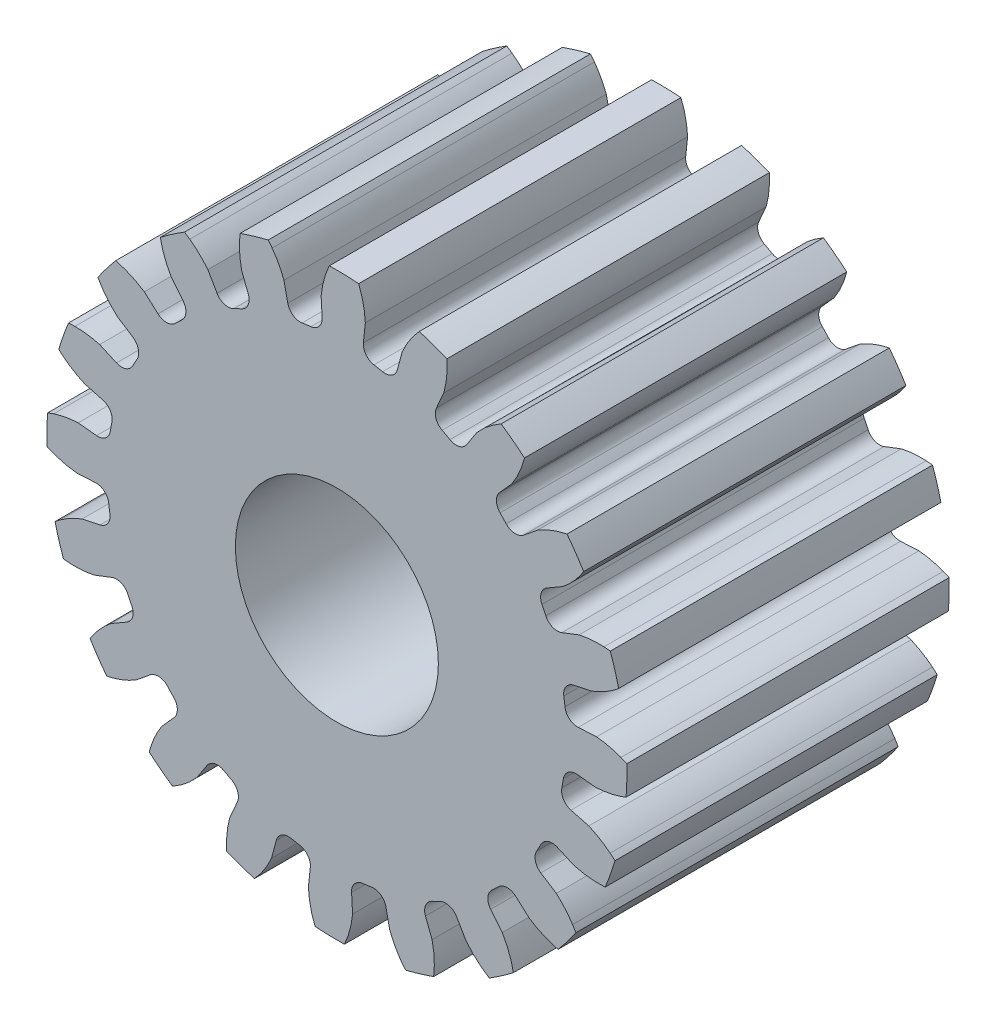
SolidWorks part; units mm, degrees
ref_plane "Front Plane" through (0, 0, 0) normal (0, 0, 1) x (1, 0, 0)
ref_plane "Top Plane" through (0, 0, 0) normal (0, 1, 0) x (1, 0, 0)
ref_plane "Right Plane" through (0, 0, 0) normal (1, 0, 0) x (0, 0, -1)
sketch "Sketch1" plane through (0, 0, 0) normal (0, 0, 1) x (1, 0, 0)
  line L0 (541.9192, -238.0328) -> (542.2005, -237.8042) construction
  line L1 (542.6706, -238.2979) -> (542.4285, -238.5677) construction
  line L2 (543.12, -239.0965) -> (543.3169, -238.7922) construction
  line L3 (543.9165, -239.1165) -> (543.7696, -239.4479) construction
  line L4 (544.5907, -239.7371) -> (544.6839, -239.3868) construction
  line L5 (545.3543, -239.5099) -> (545.317, -239.8705) construction
  line L6 (546.1873, -239.8919) -> (546.1678, -239.5299) construction
  line L7 (546.8434, -239.4398) -> (546.9194, -239.7943) construction
  line L8 (547.7537, -239.5456) -> (547.6232, -239.2074) construction
  line L9 (548.238, -238.913) -> (548.4197, -239.2266) construction
  line L10 (549.1364, -238.7323) -> (548.9078, -238.451) construction
  line L11 (549.4014, -237.981) -> (549.6712, -238.2231) construction
  line L12 (550.2001, -237.5316) -> (549.8957, -237.3346) construction
  line L13 (550.22, -236.7351) -> (550.5514, -236.882) construction
  line L14 (550.8406, -236.0609) -> (550.4903, -235.9676) construction
  line L15 (550.6134, -235.2972) -> (550.974, -235.3345) construction
  line L16 (550.9954, -234.4642) -> (550.6334, -234.4838) construction
  line L17 (550.5433, -233.8081) -> (550.8978, -233.7322) construction
  line L18 (550.6492, -232.8979) -> (550.311, -233.0283) construction
  line L19 (550.0165, -232.4136) -> (550.3301, -232.2318) construction
  line L20 (549.8359, -231.5152) -> (549.5545, -231.7438) construction
  line L21 (549.0845, -231.2501) -> (549.3266, -230.9803) construction
  line L22 (548.6351, -230.4515) -> (548.4382, -230.7558) construction
  line L23 (547.8386, -230.4316) -> (547.9855, -230.1002) construction
  line L24 (547.1644, -229.8109) -> (547.0712, -230.1612) construction
  line L25 (546.4007, -230.0381) -> (546.438, -229.6775) construction
  line L26 (545.5677, -229.6562) -> (545.5873, -230.0181) construction
  line L27 (544.9116, -230.1082) -> (544.8357, -229.7538) construction
  line L28 (544.0014, -230.0024) -> (544.1319, -230.3406) construction
  line L29 (543.5171, -230.6351) -> (543.3353, -230.3214) construction
  line L30 (542.6187, -230.8157) -> (542.8473, -231.097) construction
  line L31 (542.3536, -231.567) -> (542.0838, -231.3249) construction
  line L32 (541.555, -232.0164) -> (541.8594, -232.2134) construction
  line L33 (541.5351, -232.813) -> (541.2037, -232.6661) construction
  line L34 (540.9144, -233.4871) -> (541.2647, -233.5804) construction
  line L35 (541.1416, -234.2508) -> (540.7811, -234.2135) construction
  line L36 (540.7597, -235.0838) -> (541.1217, -235.0642) construction
  line L37 (541.2117, -235.7399) -> (540.8573, -235.8159) construction
  line L38 (541.1059, -236.6501) -> (541.4441, -236.5197) construction
  line L39 (541.7386, -237.1344) -> (541.4249, -237.3162) construction
  line L40 (541.9192, -238.0328) -> (542.2005, -237.8042)
  line L41 (542.6706, -238.2979) -> (542.4285, -238.5677)
  line L42 (543.12, -239.0965) -> (543.3169, -238.7922)
  line L43 (543.9165, -239.1165) -> (543.7696, -239.4479)
  line L44 (544.5907, -239.7371) -> (544.6839, -239.3868)
  line L45 (545.3543, -239.5099) -> (545.317, -239.8705)
  line L46 (546.1873, -239.8919) -> (546.1678, -239.5299)
  line L47 (546.8434, -239.4398) -> (546.9194, -239.7943)
  line L48 (547.7537, -239.5456) -> (547.6232, -239.2074)
  line L49 (548.238, -238.913) -> (548.4197, -239.2266)
  line L50 (549.1364, -238.7323) -> (548.9078, -238.451)
  line L51 (549.4014, -237.981) -> (549.6712, -238.2231)
  line L52 (550.2001, -237.5316) -> (549.8957, -237.3346)
  line L53 (550.22, -236.7351) -> (550.5514, -236.882)
  line L54 (550.8406, -236.0609) -> (550.4903, -235.9676)
  line L55 (550.6134, -235.2972) -> (550.974, -235.3345)
  line L56 (550.9954, -234.4642) -> (550.6334, -234.4838)
  line L57 (550.5433, -233.8081) -> (550.8978, -233.7322)
  line L58 (550.6492, -232.8979) -> (550.311, -233.0283)
  line L59 (550.0165, -232.4136) -> (550.3301, -232.2318)
  line L60 (549.8359, -231.5152) -> (549.5545, -231.7438)
  line L61 (549.0845, -231.2501) -> (549.3266, -230.9803)
  line L62 (548.6351, -230.4515) -> (548.4382, -230.7558)
  line L63 (547.8386, -230.4316) -> (547.9855, -230.1002)
  line L64 (547.1644, -229.8109) -> (547.0712, -230.1612)
  line L65 (546.4007, -230.0381) -> (546.438, -229.6775)
  line L66 (545.5677, -229.6562) -> (545.5873, -230.0181)
  line L67 (544.9116, -230.1082) -> (544.8357, -229.7538)
  line L68 (544.0014, -230.0024) -> (544.1319, -230.3406)
  line L69 (543.5171, -230.6351) -> (543.3353, -230.3214)
  line L70 (542.6187, -230.8157) -> (542.8473, -231.097)
  line L71 (542.3536, -231.567) -> (542.0838, -231.3249)
  line L72 (541.555, -232.0164) -> (541.8594, -232.2134)
  line L73 (541.5351, -232.813) -> (541.2037, -232.6661)
  line L74 (540.9144, -233.4871) -> (541.2647, -233.5804)
  line L75 (541.1416, -234.2508) -> (540.7811, -234.2135)
  line L76 (540.7597, -235.0838) -> (541.1217, -235.0642)
  line L77 (541.2117, -235.7399) -> (540.8573, -235.8159)
  line L78 (541.1059, -236.6501) -> (541.4441, -236.5197)
  line L79 (541.7386, -237.1344) -> (541.4249, -237.3162)
  arc A0 (545.4481, -240.4729) -> (546.0269, -240.4871) centre (545.8775, -234.774) ccw construction
  arc A1 (547.2301, -240.3266) -> (547.785, -240.1613) centre (545.8775, -234.774) ccw construction
  arc A2 (548.8798, -239.6369) -> (549.3564, -239.3082) centre (545.8775, -234.774) ccw construction
  arc A3 (550.2356, -238.4712) -> (550.5873, -238.0112) centre (545.8775, -234.774) ccw construction
  arc A4 (551.1647, -236.9435) -> (551.3571, -236.3974) centre (545.8775, -234.774) ccw construction
  arc A5 (551.5764, -235.2035) -> (551.5906, -234.6246) centre (545.8775, -234.774) ccw construction
  arc A6 (551.4302, -233.4214) -> (551.2648, -232.8665) centre (545.8775, -234.774) ccw construction
  arc A7 (550.7404, -231.7718) -> (550.4117, -231.2951) centre (545.8775, -234.774) ccw construction
  arc A8 (544.525, -229.2214) -> (543.97, -229.3867) centre (545.8775, -234.774) ccw construction
  arc A9 (546.307, -229.0752) -> (545.7281, -229.061) centre (545.8775, -234.774) ccw construction
  arc A10 (548.047, -229.4868) -> (547.5009, -229.2944) centre (545.8775, -234.774) ccw construction
  arc A11 (549.5747, -230.416) -> (549.1147, -230.0643) centre (545.8775, -234.774) ccw construction
  arc A12 (542.8753, -229.9111) -> (542.3986, -230.2399) centre (545.8775, -234.774) ccw construction
  arc A13 (541.5195, -231.0769) -> (541.1678, -231.5368) centre (545.8775, -234.774) ccw construction
  arc A14 (540.5903, -232.6045) -> (540.3979, -233.1507) centre (545.8775, -234.774) ccw construction
  arc A15 (540.1787, -234.3445) -> (540.1645, -234.9234) centre (545.8775, -234.774) ccw construction
  arc A16 (540.3249, -236.1266) -> (540.4903, -236.6815) centre (545.8775, -234.774) ccw construction
  arc A17 (541.0146, -237.7763) -> (541.3434, -238.2529) centre (545.8775, -234.774) ccw construction
  arc A18 (542.1804, -239.132) -> (542.6403, -239.4838) centre (545.8775, -234.774) ccw construction
  arc A19 (543.708, -240.0612) -> (544.2542, -240.2536) centre (545.8775, -234.774) ccw construction
  arc A20 (542.5419, -237.8294) -> (542.2005, -237.8042) centre (542.3579, -237.9979) ccw construction
  arc A21 (542.5419, -237.8294) -> (542.6622, -237.9557) centre (545.8775, -234.774) ccw construction
  arc A22 (542.6706, -238.2979) -> (542.6622, -237.9557) centre (542.4848, -238.1312) ccw construction
  arc A23 (543.6494, -238.7106) -> (543.3169, -238.7922) centre (543.5264, -238.9278) ccw construction
  arc A24 (543.6494, -238.7106) -> (543.8028, -238.7936) centre (545.8775, -234.774) ccw construction
  arc A25 (543.9165, -239.1165) -> (543.8028, -238.7936) centre (543.6883, -239.0153) ccw construction
  arc A26 (544.9749, -239.2065) -> (544.6839, -239.3868) centre (544.9251, -239.451) ccw construction
  arc A27 (544.9749, -239.2065) -> (545.1464, -239.238) centre (545.8775, -234.774) ccw construction
  arc A28 (545.3543, -239.5099) -> (545.1464, -239.238) centre (545.1061, -239.4842) ccw construction
  arc A29 (546.3888, -239.2685) -> (546.1678, -239.5299) centre (546.417, -239.5164) ccw construction
  arc A30 (546.3888, -239.2685) -> (546.5617, -239.2454) centre (545.8775, -234.774) ccw construction
  arc A31 (546.8434, -239.4398) -> (546.5617, -239.2454) centre (546.5994, -239.4921) ccw construction
  arc A32 (547.7526, -238.8905) -> (547.6232, -239.2074) centre (547.856, -239.1176) ccw construction
  arc A33 (547.7526, -238.8905) -> (547.9099, -238.8151) centre (545.8775, -234.774) ccw construction
  arc A34 (548.238, -238.913) -> (547.9099, -238.8151) centre (548.022, -239.0381) ccw construction
  arc A35 (548.9329, -238.1096) -> (548.9078, -238.451) centre (549.1015, -238.2936) ccw construction
  arc A36 (548.9329, -238.1096) -> (549.0592, -237.9893) centre (545.8775, -234.774) ccw construction
  arc A37 (549.4014, -237.981) -> (549.0592, -237.9893) centre (549.2348, -238.1667) ccw construction
  arc A38 (549.8141, -237.0022) -> (549.8957, -237.3346) centre (550.0313, -237.1251) ccw construction
  arc A39 (549.8141, -237.0022) -> (549.8971, -236.8488) centre (545.8775, -234.774) ccw construction
  arc A40 (550.22, -236.7351) -> (549.8971, -236.8488) centre (550.1189, -236.9632) ccw construction
  arc A41 (550.31, -235.6767) -> (550.4903, -235.9676) centre (550.5545, -235.7265) ccw construction
  arc A42 (550.31, -235.6767) -> (550.3415, -235.5051) centre (545.8775, -234.774) ccw construction
  arc A43 (550.6134, -235.2972) -> (550.3415, -235.5051) centre (550.5878, -235.5454) ccw construction
  arc A44 (550.372, -234.2628) -> (550.6334, -234.4838) centre (550.6199, -234.2346) ccw construction
  arc A45 (550.372, -234.2628) -> (550.3489, -234.0899) centre (545.8775, -234.774) ccw construction
  arc A46 (550.5433, -233.8081) -> (550.3489, -234.0899) centre (550.5956, -234.0521) ccw construction
  arc A47 (549.994, -232.899) -> (550.311, -233.0283) centre (550.2211, -232.7955) ccw construction
  arc A48 (549.994, -232.899) -> (549.9187, -232.7416) centre (545.8775, -234.774) ccw construction
  arc A49 (550.0165, -232.4136) -> (549.9187, -232.7416) centre (550.1416, -232.6295) ccw construction
  arc A50 (549.2131, -231.7187) -> (549.5545, -231.7438) centre (549.3972, -231.5501) ccw construction
  arc A51 (549.2131, -231.7187) -> (549.0928, -231.5923) centre (545.8775, -234.774) ccw construction
  arc A52 (549.0845, -231.2501) -> (549.0928, -231.5923) centre (549.2702, -231.4168) ccw construction
  arc A53 (548.1057, -230.8374) -> (548.4382, -230.7558) centre (548.2286, -230.6203) ccw construction
  arc A54 (548.1057, -230.8374) -> (547.9523, -230.7545) centre (545.8775, -234.774) ccw construction
  arc A55 (547.8386, -230.4316) -> (547.9523, -230.7545) centre (548.0668, -230.5327) ccw construction
  arc A56 (546.7802, -230.3416) -> (547.0712, -230.1612) centre (546.83, -230.097) ccw construction
  arc A57 (546.7802, -230.3416) -> (546.6086, -230.3101) centre (545.8775, -234.774) ccw construction
  arc A58 (546.4007, -230.0381) -> (546.6086, -230.3101) centre (546.649, -230.0638) ccw construction
  arc A59 (545.3663, -230.2796) -> (545.5873, -230.0181) centre (545.3381, -230.0316) ccw construction
  arc A60 (545.3663, -230.2796) -> (545.1934, -230.3026) centre (545.8775, -234.774) ccw construction
  arc A61 (544.9116, -230.1082) -> (545.1934, -230.3026) centre (545.1557, -230.0559) ccw construction
  arc A62 (544.0025, -230.6575) -> (544.1319, -230.3406) centre (543.899, -230.4304) ccw construction
  arc A63 (544.0025, -230.6575) -> (543.8452, -230.7329) centre (545.8775, -234.774) ccw construction
  arc A64 (543.5171, -230.6351) -> (543.8452, -230.7329) centre (543.733, -230.5099) ccw construction
  arc A65 (542.8222, -231.4384) -> (542.8473, -231.097) centre (542.6536, -231.2544) ccw construction
  arc A66 (542.8222, -231.4384) -> (542.6959, -231.5587) centre (545.8775, -234.774) ccw construction
  arc A67 (542.3536, -231.567) -> (542.6959, -231.5587) centre (542.5203, -231.3813) ccw construction
  arc A68 (541.941, -232.5458) -> (541.8594, -232.2134) centre (541.7238, -232.4229) ccw construction
  arc A69 (541.941, -232.5458) -> (541.858, -232.6993) centre (545.8775, -234.774) ccw construction
  arc A70 (541.5351, -232.813) -> (541.858, -232.6993) centre (541.6362, -232.5848) ccw construction
  arc A71 (541.4451, -233.8714) -> (541.2647, -233.5804) centre (541.2005, -233.8216) ccw construction
  arc A72 (541.4451, -233.8714) -> (541.4136, -234.0429) centre (545.8775, -234.774) ccw construction
  arc A73 (541.1416, -234.2508) -> (541.4136, -234.0429) centre (541.1673, -234.0026) ccw construction
  arc A74 (541.3831, -235.2852) -> (541.1217, -235.0642) centre (541.1351, -235.3134) ccw construction
  arc A75 (541.3831, -235.2852) -> (541.4061, -235.4581) centre (545.8775, -234.774) ccw construction
  arc A76 (541.2117, -235.7399) -> (541.4061, -235.4581) centre (541.1595, -235.4959) ccw construction
  arc A77 (541.761, -236.6491) -> (541.4441, -236.5197) centre (541.5339, -236.7525) ccw construction
  arc A78 (541.761, -236.6491) -> (541.8364, -236.8064) centre (545.8775, -234.774) ccw construction
  arc A79 (541.7386, -237.1344) -> (541.8364, -236.8064) centre (541.6134, -236.9185) ccw construction
  arc A80 (545.4481, -240.4729) -> (546.0269, -240.4871) centre (545.8775, -234.774) ccw
  arc A81 (547.2301, -240.3266) -> (547.785, -240.1613) centre (545.8775, -234.774) ccw
  arc A82 (548.8798, -239.6369) -> (549.3564, -239.3082) centre (545.8775, -234.774) ccw
  arc A83 (550.2356, -238.4712) -> (550.5873, -238.0112) centre (545.8775, -234.774) ccw
  arc A84 (551.1647, -236.9435) -> (551.3571, -236.3974) centre (545.8775, -234.774) ccw
  arc A85 (551.5764, -235.2035) -> (551.5906, -234.6246) centre (545.8775, -234.774) ccw
  arc A86 (551.4302, -233.4214) -> (551.2648, -232.8665) centre (545.8775, -234.774) ccw
  arc A87 (550.7404, -231.7718) -> (550.4117, -231.2951) centre (545.8775, -234.774) ccw
  arc A88 (544.525, -229.2214) -> (543.97, -229.3867) centre (545.8775, -234.774) ccw
  arc A89 (546.307, -229.0752) -> (545.7281, -229.061) centre (545.8775, -234.774) ccw
  arc A90 (548.047, -229.4868) -> (547.5009, -229.2944) centre (545.8775, -234.774) ccw
  arc A91 (549.5747, -230.416) -> (549.1147, -230.0643) centre (545.8775, -234.774) ccw
  arc A92 (542.8753, -229.9111) -> (542.3986, -230.2399) centre (545.8775, -234.774) ccw
  arc A93 (541.5195, -231.0769) -> (541.1678, -231.5368) centre (545.8775, -234.774) ccw
  arc A94 (540.5903, -232.6045) -> (540.3979, -233.1507) centre (545.8775, -234.774) ccw
  arc A95 (540.1787, -234.3445) -> (540.1645, -234.9234) centre (545.8775, -234.774) ccw
  arc A96 (540.3249, -236.1266) -> (540.4903, -236.6815) centre (545.8775, -234.774) ccw
  arc A97 (541.0146, -237.7763) -> (541.3434, -238.2529) centre (545.8775, -234.774) ccw
  arc A98 (542.1804, -239.132) -> (542.6403, -239.4838) centre (545.8775, -234.774) ccw
  arc A99 (543.708, -240.0612) -> (544.2542, -240.2536) centre (545.8775, -234.774) ccw
  arc A100 (542.5419, -237.8294) -> (542.2005, -237.8042) centre (542.3579, -237.9979) ccw
  arc A101 (542.5419, -237.8294) -> (542.6622, -237.9557) centre (545.8775, -234.774) ccw
  arc A102 (542.6706, -238.2979) -> (542.6622, -237.9557) centre (542.4848, -238.1312) ccw
  arc A103 (543.6494, -238.7106) -> (543.3169, -238.7922) centre (543.5264, -238.9278) ccw
  arc A104 (543.6494, -238.7106) -> (543.8028, -238.7936) centre (545.8775, -234.774) ccw
  arc A105 (543.9165, -239.1165) -> (543.8028, -238.7936) centre (543.6883, -239.0153) ccw
  arc A106 (544.9749, -239.2065) -> (544.6839, -239.3868) centre (544.9251, -239.451) ccw
  arc A107 (544.9749, -239.2065) -> (545.1464, -239.238) centre (545.8775, -234.774) ccw
  arc A108 (545.3543, -239.5099) -> (545.1464, -239.238) centre (545.1061, -239.4842) ccw
  arc A109 (546.3888, -239.2685) -> (546.1678, -239.5299) centre (546.417, -239.5164) ccw
  arc A110 (546.3888, -239.2685) -> (546.5617, -239.2454) centre (545.8775, -234.774) ccw
  arc A111 (546.8434, -239.4398) -> (546.5617, -239.2454) centre (546.5994, -239.4921) ccw
  arc A112 (547.7526, -238.8905) -> (547.6232, -239.2074) centre (547.856, -239.1176) ccw
  arc A113 (547.7526, -238.8905) -> (547.9099, -238.8151) centre (545.8775, -234.774) ccw
  arc A114 (548.238, -238.913) -> (547.9099, -238.8151) centre (548.022, -239.0381) ccw
  arc A115 (548.9329, -238.1096) -> (548.9078, -238.451) centre (549.1015, -238.2936) ccw
  arc A116 (548.9329, -238.1096) -> (549.0592, -237.9893) centre (545.8775, -234.774) ccw
  arc A117 (549.4014, -237.981) -> (549.0592, -237.9893) centre (549.2348, -238.1667) ccw
  arc A118 (549.8141, -237.0022) -> (549.8957, -237.3346) centre (550.0313, -237.1251) ccw
  arc A119 (549.8141, -237.0022) -> (549.8971, -236.8488) centre (545.8775, -234.774) ccw
  arc A120 (550.22, -236.7351) -> (549.8971, -236.8488) centre (550.1189, -236.9632) ccw
  arc A121 (550.31, -235.6767) -> (550.4903, -235.9676) centre (550.5545, -235.7265) ccw
  arc A122 (550.31, -235.6767) -> (550.3415, -235.5051) centre (545.8775, -234.774) ccw
  arc A123 (550.6134, -235.2972) -> (550.3415, -235.5051) centre (550.5878, -235.5454) ccw
  arc A124 (550.372, -234.2628) -> (550.6334, -234.4838) centre (550.6199, -234.2346) ccw
  arc A125 (550.372, -234.2628) -> (550.3489, -234.0899) centre (545.8775, -234.774) ccw
  arc A126 (550.5433, -233.8081) -> (550.3489, -234.0899) centre (550.5956, -234.0521) ccw
  arc A127 (549.994, -232.899) -> (550.311, -233.0283) centre (550.2211, -232.7955) ccw
  arc A128 (549.994, -232.899) -> (549.9187, -232.7416) centre (545.8775, -234.774) ccw
  arc A129 (550.0165, -232.4136) -> (549.9187, -232.7416) centre (550.1416, -232.6295) ccw
  arc A130 (549.2131, -231.7187) -> (549.5545, -231.7438) centre (549.3972, -231.5501) ccw
  arc A131 (549.2131, -231.7187) -> (549.0928, -231.5923) centre (545.8775, -234.774) ccw
  arc A132 (549.0845, -231.2501) -> (549.0928, -231.5923) centre (549.2702, -231.4168) ccw
  arc A133 (548.1057, -230.8374) -> (548.4382, -230.7558) centre (548.2286, -230.6203) ccw
  arc A134 (548.1057, -230.8374) -> (547.9523, -230.7545) centre (545.8775, -234.774) ccw
  arc A135 (547.8386, -230.4316) -> (547.9523, -230.7545) centre (548.0668, -230.5327) ccw
  arc A136 (546.7802, -230.3416) -> (547.0712, -230.1612) centre (546.83, -230.097) ccw
  arc A137 (546.7802, -230.3416) -> (546.6086, -230.3101) centre (545.8775, -234.774) ccw
  arc A138 (546.4007, -230.0381) -> (546.6086, -230.3101) centre (546.649, -230.0638) ccw
  arc A139 (545.3663, -230.2796) -> (545.5873, -230.0181) centre (545.3381, -230.0316) ccw
  arc A140 (545.3663, -230.2796) -> (545.1934, -230.3026) centre (545.8775, -234.774) ccw
  arc A141 (544.9116, -230.1082) -> (545.1934, -230.3026) centre (545.1557, -230.0559) ccw
  arc A142 (544.0025, -230.6575) -> (544.1319, -230.3406) centre (543.899, -230.4304) ccw
  arc A143 (544.0025, -230.6575) -> (543.8452, -230.7329) centre (545.8775, -234.774) ccw
  arc A144 (543.5171, -230.6351) -> (543.8452, -230.7329) centre (543.733, -230.5099) ccw
  arc A145 (542.8222, -231.4384) -> (542.8473, -231.097) centre (542.6536, -231.2544) ccw
  arc A146 (542.8222, -231.4384) -> (542.6959, -231.5587) centre (545.8775, -234.774) ccw
  arc A147 (542.3536, -231.567) -> (542.6959, -231.5587) centre (542.5203, -231.3813) ccw
  arc A148 (541.941, -232.5458) -> (541.8594, -232.2134) centre (541.7238, -232.4229) ccw
  arc A149 (541.941, -232.5458) -> (541.858, -232.6993) centre (545.8775, -234.774) ccw
  arc A150 (541.5351, -232.813) -> (541.858, -232.6993) centre (541.6362, -232.5848) ccw
  arc A151 (541.4451, -233.8714) -> (541.2647, -233.5804) centre (541.2005, -233.8216) ccw
  arc A152 (541.4451, -233.8714) -> (541.4136, -234.0429) centre (545.8775, -234.774) ccw
  arc A153 (541.1416, -234.2508) -> (541.4136, -234.0429) centre (541.1673, -234.0026) ccw
  arc A154 (541.3831, -235.2852) -> (541.1217, -235.0642) centre (541.1351, -235.3134) ccw
  arc A155 (541.3831, -235.2852) -> (541.4061, -235.4581) centre (545.8775, -234.774) ccw
  arc A156 (541.2117, -235.7399) -> (541.4061, -235.4581) centre (541.1595, -235.4959) ccw
  arc A157 (541.761, -236.6491) -> (541.4441, -236.5197) centre (541.5339, -236.7525) ccw
  arc A158 (541.761, -236.6491) -> (541.8364, -236.8064) centre (545.8775, -234.774) ccw
  arc A159 (541.7386, -237.1344) -> (541.8364, -236.8064) centre (541.6134, -236.9185) ccw
  circle A160 centre (545.8775, -234.774) radius 2
  parabola Q0 (546.0269, -240.4871) -> (546.0759, -240.3712) focus (545.2632, -239.9821) apex (546.1224, -240.2332) construction
  parabola Q1 (545.4048, -240.3547) -> (545.4481, -240.4729) focus (546.2357, -240.006) apex (545.3652, -240.2147) construction
  parabola Q2 (547.785, -240.1613) -> (547.7958, -240.036) focus (546.9026, -239.9171) apex (547.7974, -239.8904) construction
  parabola Q3 (547.1525, -240.2277) -> (547.2301, -240.3266) focus (547.8349, -239.6393) apex (547.0715, -240.1067) construction
  parabola Q4 (549.3564, -239.3082) -> (549.328, -239.1856) focus (548.4418, -239.3486) apex (549.2845, -239.0467) construction
  parabola Q5 (548.7754, -239.5668) -> (548.8798, -239.6369) focus (549.2426, -238.7963) apex (548.661, -239.4767) construction
  parabola Q6 (550.5873, -238.0112) -> (550.5224, -237.9035) focus (549.7299, -238.3323) apex (550.4381, -237.7848) construction
  parabola Q7 (550.1146, -238.4367) -> (550.2356, -238.4712) focus (550.3208, -237.5596) apex (549.978, -238.3865) construction
  parabola Q8 (551.3571, -236.3974) -> (551.2621, -236.315) focus (550.6409, -236.9677) apex (551.1452, -236.2282) construction
  parabola Q9 (551.039, -236.9481) -> (551.1647, -236.9435) focus (550.9641, -236.0502) apex (550.8936, -236.9425) construction
  parabola Q10 (551.5906, -234.6246) -> (551.4747, -234.5756) focus (551.0857, -235.3884) apex (551.3368, -234.5292) construction
  parabola Q11 (551.4583, -235.2467) -> (551.5764, -235.2035) focus (551.1095, -234.4159) apex (551.3182, -235.2864) construction
  parabola Q12 (551.2648, -232.8665) -> (551.1395, -232.8557) focus (551.0206, -233.7489) apex (550.9939, -232.8542) construction
  parabola Q13 (551.3312, -233.4991) -> (551.4302, -233.4214) focus (550.7428, -232.8166) apex (551.2102, -233.58) construction
  parabola Q14 (550.4117, -231.2951) -> (550.2892, -231.3236) focus (550.4521, -232.2098) apex (550.1502, -231.3671) construction
  parabola Q15 (550.6703, -231.8762) -> (550.7404, -231.7718) focus (549.8998, -231.409) apex (550.5803, -231.9906) construction
  parabola Q16 (543.97, -229.3867) -> (543.9593, -229.5121) focus (544.8524, -229.6309) apex (543.9577, -229.6576) construction
  parabola Q17 (544.6026, -229.3204) -> (544.525, -229.2214) focus (543.9202, -229.9087) apex (544.6836, -229.4413) construction
  parabola Q18 (545.7281, -229.061) -> (545.6792, -229.1768) focus (546.4919, -229.5659) apex (545.6327, -229.3148) construction
  parabola Q19 (546.3502, -229.1933) -> (546.307, -229.0752) focus (545.5194, -229.542) apex (546.3899, -229.3334) construction
  parabola Q20 (547.5009, -229.2944) -> (547.4185, -229.3895) focus (548.0712, -230.0106) apex (547.3317, -229.5063) construction
  parabola Q21 (548.0516, -229.6125) -> (548.047, -229.4868) focus (547.1537, -229.6874) apex (548.0461, -229.758) construction
  parabola Q22 (549.1147, -230.0643) -> (549.007, -230.1292) focus (549.4358, -230.9217) apex (548.8883, -230.2135) construction
  parabola Q23 (549.5402, -230.537) -> (549.5747, -230.416) focus (548.6631, -230.3307) apex (549.49, -230.6736) construction
  parabola Q24 (542.3986, -230.2399) -> (542.4271, -230.3624) focus (543.3133, -230.1994) apex (542.4706, -230.5013) construction
  parabola Q25 (542.9797, -229.9813) -> (542.8753, -229.9111) focus (542.5125, -230.7517) apex (543.0941, -230.0713) construction
  parabola Q26 (541.1678, -231.5368) -> (541.2327, -231.6446) focus (542.0252, -231.2157) apex (541.317, -231.7632) construction
  parabola Q27 (541.6405, -231.1113) -> (541.5195, -231.0769) focus (541.4343, -231.9884) apex (541.7771, -231.1616) construction
  parabola Q28 (540.3979, -233.1507) -> (540.493, -233.233) focus (541.1142, -232.5803) apex (540.6098, -233.3199) construction
  parabola Q29 (540.716, -232.5999) -> (540.5903, -232.6045) focus (540.7909, -233.4978) apex (540.8615, -232.6055) construction
  parabola Q30 (540.1645, -234.9234) -> (540.2804, -234.9724) focus (540.6694, -234.1596) apex (540.4183, -235.0189) construction
  parabola Q31 (540.2968, -234.3013) -> (540.1787, -234.3445) focus (540.6455, -235.1321) apex (540.4369, -234.2617) construction
  parabola Q32 (540.4903, -236.6815) -> (540.6156, -236.6923) focus (540.7345, -235.7991) apex (540.7612, -236.6939) construction
  parabola Q33 (540.4239, -236.049) -> (540.3249, -236.1266) focus (541.0123, -236.7314) apex (540.5449, -235.968) construction
  parabola Q34 (541.3434, -238.2529) -> (541.4659, -238.2244) focus (541.303, -237.3382) apex (541.6048, -238.1809) construction
  parabola Q35 (541.0848, -237.6718) -> (541.0146, -237.7763) focus (541.8553, -238.139) apex (541.1748, -237.5574) construction
  parabola Q36 (542.2148, -239.0111) -> (542.1804, -239.132) focus (543.092, -239.2173) apex (542.2651, -238.8744) construction
  parabola Q37 (542.6403, -239.4838) -> (542.7481, -239.4188) focus (542.3192, -238.6264) apex (542.8668, -239.3345) construction
  parabola Q38 (544.2542, -240.2536) -> (544.3366, -240.1586) focus (543.6838, -239.5374) apex (544.4234, -240.0417) construction
  parabola Q39 (543.7034, -239.9355) -> (543.708, -240.0612) focus (544.6014, -239.8606) apex (543.709, -239.79) construction
  parabola Q40 (541.4659, -238.2244) -> (541.9192, -238.0328) focus (541.303, -237.3382) apex (541.6048, -238.1809) construction
  parabola Q41 (542.4285, -238.5677) -> (542.2148, -239.0111) focus (543.092, -239.2173) apex (542.2651, -238.8744) construction
  parabola Q42 (542.7481, -239.4188) -> (543.12, -239.0965) focus (542.3192, -238.6264) apex (542.8668, -239.3345) construction
  parabola Q43 (543.7696, -239.4479) -> (543.7034, -239.9355) focus (544.6014, -239.8606) apex (543.709, -239.79) construction
  parabola Q44 (544.3366, -240.1586) -> (544.5907, -239.7371) focus (543.6838, -239.5374) apex (544.4234, -240.0417) construction
  parabola Q45 (545.317, -239.8705) -> (545.4048, -240.3547) focus (546.2357, -240.006) apex (545.3652, -240.2147) construction
  parabola Q46 (546.0759, -240.3712) -> (546.1873, -239.8919) focus (545.2632, -239.9821) apex (546.1224, -240.2332) construction
  parabola Q47 (546.9194, -239.7943) -> (547.1525, -240.2277) focus (547.8349, -239.6393) apex (547.0715, -240.1067) construction
  parabola Q48 (547.7958, -240.036) -> (547.7537, -239.5456) focus (546.9026, -239.9171) apex (547.7974, -239.8904) construction
  parabola Q49 (548.4197, -239.2266) -> (548.7754, -239.5668) focus (549.2426, -238.7963) apex (548.661, -239.4767) construction
  parabola Q50 (549.328, -239.1856) -> (549.1364, -238.7323) focus (548.4418, -239.3486) apex (549.2845, -239.0467) construction
  parabola Q51 (549.6712, -238.2231) -> (550.1146, -238.4367) focus (550.3208, -237.5596) apex (549.978, -238.3865) construction
  parabola Q52 (550.5224, -237.9035) -> (550.2001, -237.5316) focus (549.7299, -238.3323) apex (550.4381, -237.7848) construction
  parabola Q53 (550.5514, -236.882) -> (551.039, -236.9481) focus (550.9641, -236.0502) apex (550.8936, -236.9425) construction
  parabola Q54 (551.2621, -236.315) -> (550.8406, -236.0609) focus (550.6409, -236.9677) apex (551.1452, -236.2282) construction
  parabola Q55 (550.974, -235.3345) -> (551.4583, -235.2467) focus (551.1095, -234.4159) apex (551.3182, -235.2864) construction
  parabola Q56 (551.4747, -234.5756) -> (550.9954, -234.4642) focus (551.0857, -235.3884) apex (551.3368, -234.5292) construction
  parabola Q57 (550.8978, -233.7322) -> (551.3312, -233.4991) focus (550.7428, -232.8166) apex (551.2102, -233.58) construction
  parabola Q58 (551.1395, -232.8557) -> (550.6492, -232.8979) focus (551.0206, -233.7489) apex (550.9939, -232.8542) construction
  parabola Q59 (550.3301, -232.2318) -> (550.6703, -231.8762) focus (549.8998, -231.409) apex (550.5803, -231.9906) construction
  parabola Q60 (550.2892, -231.3236) -> (549.8359, -231.5152) focus (550.4521, -232.2098) apex (550.1502, -231.3671) construction
  parabola Q61 (549.3266, -230.9803) -> (549.5402, -230.537) focus (548.6631, -230.3307) apex (549.49, -230.6736) construction
  parabola Q62 (549.007, -230.1292) -> (548.6351, -230.4515) focus (549.4358, -230.9217) apex (548.8883, -230.2135) construction
  parabola Q63 (547.9855, -230.1002) -> (548.0516, -229.6125) focus (547.1537, -229.6874) apex (548.0461, -229.758) construction
  parabola Q64 (547.4185, -229.3895) -> (547.1644, -229.8109) focus (548.0712, -230.0106) apex (547.3317, -229.5063) construction
  parabola Q65 (546.438, -229.6775) -> (546.3502, -229.1933) focus (545.5194, -229.542) apex (546.3899, -229.3334) construction
  parabola Q66 (545.6792, -229.1768) -> (545.5677, -229.6562) focus (546.4919, -229.5659) apex (545.6327, -229.3148) construction
  parabola Q67 (544.8357, -229.7538) -> (544.6026, -229.3204) focus (543.9202, -229.9087) apex (544.6836, -229.4413) construction
  parabola Q68 (543.9593, -229.5121) -> (544.0014, -230.0024) focus (544.8524, -229.6309) apex (543.9577, -229.6576) construction
  parabola Q69 (543.3353, -230.3214) -> (542.9797, -229.9813) focus (542.5125, -230.7517) apex (543.0941, -230.0713) construction
  parabola Q70 (542.4271, -230.3624) -> (542.6187, -230.8157) focus (543.3133, -230.1994) apex (542.4706, -230.5013) construction
  parabola Q71 (542.0838, -231.3249) -> (541.6405, -231.1113) focus (541.4343, -231.9884) apex (541.7771, -231.1616) construction
  parabola Q72 (541.2327, -231.6446) -> (541.555, -232.0164) focus (542.0252, -231.2157) apex (541.317, -231.7632) construction
  parabola Q73 (541.2037, -232.6661) -> (540.716, -232.5999) focus (540.7909, -233.4978) apex (540.8615, -232.6055) construction
  parabola Q74 (540.493, -233.233) -> (540.9144, -233.4871) focus (541.1142, -232.5803) apex (540.6098, -233.3199) construction
  parabola Q75 (540.7811, -234.2135) -> (540.2968, -234.3013) focus (540.6455, -235.1321) apex (540.4369, -234.2617) construction
  parabola Q76 (540.2804, -234.9724) -> (540.7597, -235.0838) focus (540.6694, -234.1596) apex (540.4183, -235.0189) construction
  parabola Q77 (540.8573, -235.8159) -> (540.4239, -236.049) focus (541.0123, -236.7314) apex (540.5449, -235.968) construction
  parabola Q78 (540.6156, -236.6923) -> (541.1059, -236.6501) focus (540.7345, -235.7991) apex (540.7612, -236.6939) construction
  parabola Q79 (541.4249, -237.3162) -> (541.0848, -237.6718) focus (541.8553, -238.139) apex (541.1748, -237.5574) construction
  parabola Q80 (546.0269, -240.4871) -> (546.0759, -240.3712) focus (545.2632, -239.9821) apex (546.1224, -240.2332)
  parabola Q81 (545.4048, -240.3547) -> (545.4481, -240.4729) focus (546.2357, -240.006) apex (545.3652, -240.2147)
  parabola Q82 (547.785, -240.1613) -> (547.7958, -240.036) focus (546.9026, -239.9171) apex (547.7974, -239.8904)
  parabola Q83 (547.1525, -240.2277) -> (547.2301, -240.3266) focus (547.8349, -239.6393) apex (547.0715, -240.1067)
  parabola Q84 (549.3564, -239.3082) -> (549.328, -239.1856) focus (548.4418, -239.3486) apex (549.2845, -239.0467)
  parabola Q85 (548.7754, -239.5668) -> (548.8798, -239.6369) focus (549.2426, -238.7963) apex (548.661, -239.4767)
  parabola Q86 (550.5873, -238.0112) -> (550.5224, -237.9035) focus (549.7299, -238.3323) apex (550.4381, -237.7848)
  parabola Q87 (550.1146, -238.4367) -> (550.2356, -238.4712) focus (550.3208, -237.5596) apex (549.978, -238.3865)
  parabola Q88 (551.3571, -236.3974) -> (551.2621, -236.315) focus (550.6409, -236.9677) apex (551.1452, -236.2282)
  parabola Q89 (551.039, -236.9481) -> (551.1647, -236.9435) focus (550.9641, -236.0502) apex (550.8936, -236.9425)
  parabola Q90 (551.5906, -234.6246) -> (551.4747, -234.5756) focus (551.0857, -235.3884) apex (551.3368, -234.5292)
  parabola Q91 (551.4583, -235.2467) -> (551.5764, -235.2035) focus (551.1095, -234.4159) apex (551.3182, -235.2864)
  parabola Q92 (551.2648, -232.8665) -> (551.1395, -232.8557) focus (551.0206, -233.7489) apex (550.9939, -232.8542)
  parabola Q93 (551.3312, -233.4991) -> (551.4302, -233.4214) focus (550.7428, -232.8166) apex (551.2102, -233.58)
  parabola Q94 (550.4117, -231.2951) -> (550.2892, -231.3236) focus (550.4521, -232.2098) apex (550.1502, -231.3671)
  parabola Q95 (550.6703, -231.8762) -> (550.7404, -231.7718) focus (549.8998, -231.409) apex (550.5803, -231.9906)
  parabola Q96 (543.97, -229.3867) -> (543.9593, -229.5121) focus (544.8524, -229.6309) apex (543.9577, -229.6576)
  parabola Q97 (544.6026, -229.3204) -> (544.525, -229.2214) focus (543.9202, -229.9087) apex (544.6836, -229.4413)
  parabola Q98 (545.7281, -229.061) -> (545.6792, -229.1768) focus (546.4919, -229.5659) apex (545.6327, -229.3148)
  parabola Q99 (546.3502, -229.1933) -> (546.307, -229.0752) focus (545.5194, -229.542) apex (546.3899, -229.3334)
  parabola Q100 (547.5009, -229.2944) -> (547.4185, -229.3895) focus (548.0712, -230.0106) apex (547.3317, -229.5063)
  parabola Q101 (548.0516, -229.6125) -> (548.047, -229.4868) focus (547.1537, -229.6874) apex (548.0461, -229.758)
  parabola Q102 (549.1147, -230.0643) -> (549.007, -230.1292) focus (549.4358, -230.9217) apex (548.8883, -230.2135)
  parabola Q103 (549.5402, -230.537) -> (549.5747, -230.416) focus (548.6631, -230.3307) apex (549.49, -230.6736)
  parabola Q104 (542.3986, -230.2399) -> (542.4271, -230.3624) focus (543.3133, -230.1994) apex (542.4706, -230.5013)
  parabola Q105 (542.9797, -229.9813) -> (542.8753, -229.9111) focus (542.5125, -230.7517) apex (543.0941, -230.0713)
  parabola Q106 (541.1678, -231.5368) -> (541.2327, -231.6446) focus (542.0252, -231.2157) apex (541.317, -231.7632)
  parabola Q107 (541.6405, -231.1113) -> (541.5195, -231.0769) focus (541.4343, -231.9884) apex (541.7771, -231.1616)
  parabola Q108 (540.3979, -233.1507) -> (540.493, -233.233) focus (541.1142, -232.5803) apex (540.6098, -233.3199)
  parabola Q109 (540.716, -232.5999) -> (540.5903, -232.6045) focus (540.7909, -233.4978) apex (540.8615, -232.6055)
  parabola Q110 (540.1645, -234.9234) -> (540.2804, -234.9724) focus (540.6694, -234.1596) apex (540.4183, -235.0189)
  parabola Q111 (540.2968, -234.3013) -> (540.1787, -234.3445) focus (540.6455, -235.1321) apex (540.4369, -234.2617)
  parabola Q112 (540.4903, -236.6815) -> (540.6156, -236.6923) focus (540.7345, -235.7991) apex (540.7612, -236.6939)
  parabola Q113 (540.4239, -236.049) -> (540.3249, -236.1266) focus (541.0123, -236.7314) apex (540.5449, -235.968)
  parabola Q114 (541.3434, -238.2529) -> (541.4659, -238.2244) focus (541.303, -237.3382) apex (541.6048, -238.1809)
  parabola Q115 (541.0848, -237.6718) -> (541.0146, -237.7763) focus (541.8553, -238.139) apex (541.1748, -237.5574)
  parabola Q116 (542.2148, -239.0111) -> (542.1804, -239.132) focus (543.092, -239.2173) apex (542.2651, -238.8744)
  parabola Q117 (542.6403, -239.4838) -> (542.7481, -239.4188) focus (542.3192, -238.6264) apex (542.8668, -239.3345)
  parabola Q118 (544.2542, -240.2536) -> (544.3366, -240.1586) focus (543.6838, -239.5374) apex (544.4234, -240.0417)
  parabola Q119 (543.7034, -239.9355) -> (543.708, -240.0612) focus (544.6014, -239.8606) apex (543.709, -239.79)
  parabola Q120 (541.4659, -238.2244) -> (541.9192, -238.0328) focus (541.303, -237.3382) apex (541.6048, -238.1809)
  parabola Q121 (542.4285, -238.5677) -> (542.2148, -239.0111) focus (543.092, -239.2173) apex (542.2651, -238.8744)
  parabola Q122 (542.7481, -239.4188) -> (543.12, -239.0965) focus (542.3192, -238.6264) apex (542.8668, -239.3345)
  parabola Q123 (543.7696, -239.4479) -> (543.7034, -239.9355) focus (544.6014, -239.8606) apex (543.709, -239.79)
  parabola Q124 (544.3366, -240.1586) -> (544.5907, -239.7371) focus (543.6838, -239.5374) apex (544.4234, -240.0417)
  parabola Q125 (545.317, -239.8705) -> (545.4048, -240.3547) focus (546.2357, -240.006) apex (545.3652, -240.2147)
  parabola Q126 (546.0759, -240.3712) -> (546.1873, -239.8919) focus (545.2632, -239.9821) apex (546.1224, -240.2332)
  parabola Q127 (546.9194, -239.7943) -> (547.1525, -240.2277) focus (547.8349, -239.6393) apex (547.0715, -240.1067)
  parabola Q128 (547.7958, -240.036) -> (547.7537, -239.5456) focus (546.9026, -239.9171) apex (547.7974, -239.8904)
  parabola Q129 (548.4197, -239.2266) -> (548.7754, -239.5668) focus (549.2426, -238.7963) apex (548.661, -239.4767)
  parabola Q130 (549.328, -239.1856) -> (549.1364, -238.7323) focus (548.4418, -239.3486) apex (549.2845, -239.0467)
  parabola Q131 (549.6712, -238.2231) -> (550.1146, -238.4367) focus (550.3208, -237.5596) apex (549.978, -238.3865)
  parabola Q132 (550.5224, -237.9035) -> (550.2001, -237.5316) focus (549.7299, -238.3323) apex (550.4381, -237.7848)
  parabola Q133 (550.5514, -236.882) -> (551.039, -236.9481) focus (550.9641, -236.0502) apex (550.8936, -236.9425)
  parabola Q134 (551.2621, -236.315) -> (550.8406, -236.0609) focus (550.6409, -236.9677) apex (551.1452, -236.2282)
  parabola Q135 (550.974, -235.3345) -> (551.4583, -235.2467) focus (551.1095, -234.4159) apex (551.3182, -235.2864)
  parabola Q136 (551.4747, -234.5756) -> (550.9954, -234.4642) focus (551.0857, -235.3884) apex (551.3368, -234.5292)
  parabola Q137 (550.8978, -233.7322) -> (551.3312, -233.4991) focus (550.7428, -232.8166) apex (551.2102, -233.58)
  parabola Q138 (551.1395, -232.8557) -> (550.6492, -232.8979) focus (551.0206, -233.7489) apex (550.9939, -232.8542)
  parabola Q139 (550.3301, -232.2318) -> (550.6703, -231.8762) focus (549.8998, -231.409) apex (550.5803, -231.9906)
  parabola Q140 (550.2892, -231.3236) -> (549.8359, -231.5152) focus (550.4521, -232.2098) apex (550.1502, -231.3671)
  parabola Q141 (549.3266, -230.9803) -> (549.5402, -230.537) focus (548.6631, -230.3307) apex (549.49, -230.6736)
  parabola Q142 (549.007, -230.1292) -> (548.6351, -230.4515) focus (549.4358, -230.9217) apex (548.8883, -230.2135)
  parabola Q143 (547.9855, -230.1002) -> (548.0516, -229.6125) focus (547.1537, -229.6874) apex (548.0461, -229.758)
  parabola Q144 (547.4185, -229.3895) -> (547.1644, -229.8109) focus (548.0712, -230.0106) apex (547.3317, -229.5063)
  parabola Q145 (546.438, -229.6775) -> (546.3502, -229.1933) focus (545.5194, -229.542) apex (546.3899, -229.3334)
  parabola Q146 (545.6792, -229.1768) -> (545.5677, -229.6562) focus (546.4919, -229.5659) apex (545.6327, -229.3148)
  parabola Q147 (544.8357, -229.7538) -> (544.6026, -229.3204) focus (543.9202, -229.9087) apex (544.6836, -229.4413)
  parabola Q148 (543.9593, -229.5121) -> (544.0014, -230.0024) focus (544.8524, -229.6309) apex (543.9577, -229.6576)
  parabola Q149 (543.3353, -230.3214) -> (542.9797, -229.9813) focus (542.5125, -230.7517) apex (543.0941, -230.0713)
  parabola Q150 (542.4271, -230.3624) -> (542.6187, -230.8157) focus (543.3133, -230.1994) apex (542.4706, -230.5013)
  parabola Q151 (542.0838, -231.3249) -> (541.6405, -231.1113) focus (541.4343, -231.9884) apex (541.7771, -231.1616)
  parabola Q152 (541.2327, -231.6446) -> (541.555, -232.0164) focus (542.0252, -231.2157) apex (541.317, -231.7632)
  parabola Q153 (541.2037, -232.6661) -> (540.716, -232.5999) focus (540.7909, -233.4978) apex (540.8615, -232.6055)
  parabola Q154 (540.493, -233.233) -> (540.9144, -233.4871) focus (541.1142, -232.5803) apex (540.6098, -233.3199)
  parabola Q155 (540.7811, -234.2135) -> (540.2968, -234.3013) focus (540.6455, -235.1321) apex (540.4369, -234.2617)
  parabola Q156 (540.2804, -234.9724) -> (540.7597, -235.0838) focus (540.6694, -234.1596) apex (540.4183, -235.0189)
  parabola Q157 (540.8573, -235.8159) -> (540.4239, -236.049) focus (541.0123, -236.7314) apex (540.5449, -235.968)
  parabola Q158 (540.6156, -236.6923) -> (541.1059, -236.6501) focus (540.7345, -235.7991) apex (540.7612, -236.6939)
  parabola Q159 (541.4249, -237.3162) -> (541.0848, -237.6718) focus (541.8553, -238.139) apex (541.1748, -237.5574)
  dimension "D1" = 4
extrude "Boss-Extrude1" add sketch "Sketch1" along normal blind 6.35
sketch "Sketch2" plane through (0, 0, 6.35) normal (0, 0, 1) x (1, 0, 0)
  circle A0 centre (545.0173, -231.433) radius 0.75 construction
  circle A1 centre (546.7377, -238.1151) radius 0.75 construction
  circle A2 centre (545.0173, -231.433) radius 0.75
  circle A3 centre (546.7377, -238.1151) radius 0.75
